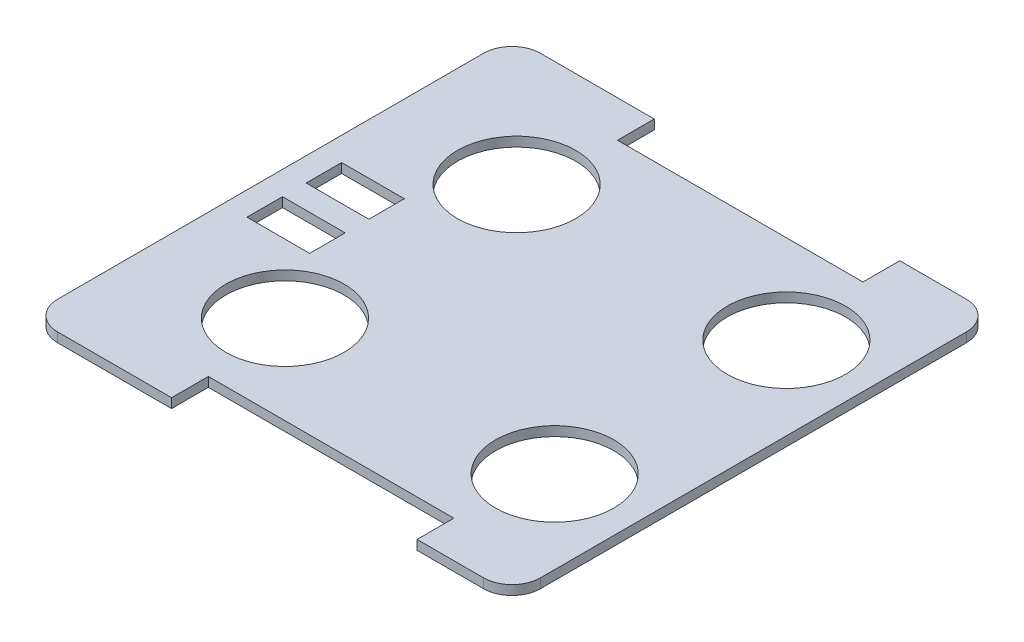
SolidWorks part; units mm, degrees
material "Aleación 1060"
ref_plane "Alzado" through (0, 0, 0) normal (0, 0, 1) x (1, 0, 0)
ref_plane "Planta" through (0, 0, 0) normal (0, 1, 0) x (1, 0, 0)
ref_plane "Vista lateral" through (0, 0, 0) normal (1, 0, 0) x (0, 0, -1)
ref_plane "Plano1" through (0, 54.7071, 0) normal (0, 1, 0) x (1, 0, 0)
sketch "Croquis1" plane through (0, 54.7071, 0) normal (0, 1, 0) x (1, 0, 0)
  line L48 (-135.857, -92.1) -> (-135.857, -55) construction
  line L55 (-135.857, -92.1) -> (71.653, -92.1) construction
  line L63 (71.653, -92.1) -> (71.653, -55) construction
  line L72 (71.653, -437.9) -> (71.653, -475) construction
  line L82 (-135.857, -437.9) -> (71.653, -437.9) construction
  line L93 (-135.857, -437.9) -> (-135.857, -475) construction
  line L105 (-232.102, -61.0045) -> (-135.857, -61.0045) construction
  line L106 (71.653, -61.0045) -> (127.898, -61.0045) construction
  line L107 (151.8935, -85) -> (151.8935, -445) construction
  line L108 (127.898, -468.9955) -> (71.653, -468.9955) construction
  line L109 (-135.857, -468.9955) -> (-232.102, -468.9955) construction
  line L110 (-256.0976, -445) -> (-256.0976, -85) construction
  line L111 (-135.857, -92.1) -> (71.653, -92.1)
  line L112 (71.653, -437.9) -> (71.653, -468.9955)
  line L113 (-135.857, -437.9) -> (71.653, -437.9)
  line L114 (-135.857, -437.9) -> (-135.857, -468.9955)
  line L115 (-135.857, -92.1) -> (-135.857, -61.0045)
  line L116 (71.653, -92.1) -> (71.653, -61.0045)
  line L117 (-232.102, -61.0045) -> (-135.857, -61.0045)
  line L118 (71.653, -61.0045) -> (127.898, -61.0045)
  line L119 (151.8935, -85) -> (151.8935, -445)
  line L120 (127.898, -468.9955) -> (71.653, -468.9955)
  line L121 (-135.857, -468.9955) -> (-232.102, -468.9955)
  line L122 (-256.0976, -445) -> (-256.0976, -85)
  arc A56 (-232.102, -61.0045) -> (-256.0976, -85) centre (-232.102, -85) ccw construction
  arc A57 (151.8935, -85) -> (127.898, -61.0045) centre (127.898, -85) ccw construction
  arc A58 (127.898, -468.9955) -> (151.8935, -445) centre (127.898, -445) ccw construction
  arc A59 (-256.0976, -445) -> (-232.102, -468.9955) centre (-232.102, -445) ccw construction
  arc A60 (-232.102, -61.0045) -> (-256.0976, -85) centre (-232.102, -85) ccw
  arc A61 (151.8935, -85) -> (127.898, -61.0045) centre (127.898, -85) ccw
  arc A62 (127.898, -468.9955) -> (151.8935, -445) centre (127.898, -445) ccw
  arc A63 (-256.0976, -445) -> (-232.102, -468.9955) centre (-232.102, -445) ccw
extrude "Saliente-Extruir1" add sketch "Croquis1" along normal mid plane 8 contours L113 L112 L120 A62 L119 A61 L118 L116 L111 L115 L117 A60 L122 A63 L121 L114
sketch "Croquis2" plane through (0, 58.7071, 0) normal (0, 1, 0) x (1, 0, 0)
  line L0 (-32.102, -92.1) -> (-32.102, -437.9) construction
  line L5 (71.653, -92.1) -> (-135.857, -92.1) construction
  line L6 (51.8935, -167.1) -> (111.8935, -167.1) construction
  line L11 (-256.0976, -265) -> (151.8935, -265) construction
  line L12 (-92.102, -92.1) -> (27.898, -92.1) construction
  line L13 (-92.102, -92.1) -> (-92.102, -244.5) construction
  line L14 (-92.102, -244.5) -> (27.898, -244.5) construction
  line L15 (27.898, -92.1) -> (27.898, -244.5) construction
  line L16 (-256.0976, -85) -> (-256.0976, -445) construction
  line L17 (151.8935, -445) -> (151.8935, -85) construction
  line L18 (-92.102, -285.5) -> (27.898, -285.5) construction
  line L19 (27.898, -437.9) -> (27.898, -285.5) construction
  line L20 (-92.102, -437.9) -> (27.898, -437.9) construction
  line L21 (-92.102, -437.9) -> (-92.102, -285.5) construction
  line L26 (111.8935, -237.1) -> (111.8935, -97.1) construction
  line L27 (51.8935, -97.1) -> (111.8935, -97.1) construction
  line L28 (51.8935, -237.1) -> (51.8935, -97.1) construction
  line L29 (51.8935, -237.1) -> (111.8935, -237.1) construction
  line L30 (-256.0976, -290) -> (-244.6304, -290) construction
  line L31 (-256.0976, -290) -> (-256.0976, -240) construction
  line L32 (-256.0976, -240) -> (-244.6304, -240) construction
  line L33 (-244.6304, -290) -> (-244.6304, -240) construction
  line L39 (-116.0976, -237.1) -> (-176.0976, -237.1) construction
  line L40 (-116.0976, -237.1) -> (-116.0976, -97.1) construction
  line L41 (-116.0976, -97.1) -> (-176.0976, -97.1) construction
  line L42 (-176.0976, -237.1) -> (-176.0976, -97.1) construction
  line L43 (-116.0976, -167.1) -> (-176.0976, -167.1) construction
  line L44 (51.8935, -292.9) -> (111.8935, -292.9) construction
  line L45 (51.8935, -292.9) -> (51.8935, -432.9) construction
  line L46 (51.8935, -432.9) -> (111.8935, -432.9) construction
  line L47 (111.8935, -292.9) -> (111.8935, -432.9) construction
  line L48 (51.8935, -362.9) -> (111.8935, -362.9) construction
  line L49 (-116.0976, -362.9) -> (-176.0976, -362.9) construction
  line L50 (-176.0976, -292.9) -> (-176.0976, -432.9) construction
  line L51 (-116.0976, -432.9) -> (-176.0976, -432.9) construction
  line L52 (-116.0976, -292.9) -> (-116.0976, -432.9) construction
  line L53 (-116.0976, -292.9) -> (-176.0976, -292.9) construction
  line L55 (-236.0976, -275) -> (-183.0976, -275)
  line L56 (-236.0976, -275) -> (-236.0976, -305)
  line L57 (-236.0976, -305) -> (-183.0976, -305)
  line L58 (-183.0976, -275) -> (-183.0976, -305)
  line L62 (-236.0976, -225) -> (-183.0976, -225)
  line L63 (-183.0976, -255) -> (-183.0976, -225)
  line L64 (-236.0976, -255) -> (-183.0976, -255)
  line L65 (-236.0976, -255) -> (-236.0976, -225)
  circle A0 centre (-146.0976, -167.1) radius 50
  circle A1 centre (81.8935, -167.1) radius 50
  circle A3 centre (81.8935, -362.9) radius 50
  circle A4 centre (-146.0976, -362.9) radius 50
  point P3 (-32.102, -437.9)
  point P44 (-256.0976, -265)
  point P51 (-32.102, -92.1)
  point P52 (-32.102, -92.1)
  point P61 (131.8935, -167.1)
  point P67 (-236.0976, -290)
  dimension "D6" = 100
  dimension "D1" = 60
  dimension "D2" = 140
  dimension "D3" = 152.4
  dimension "D4" = 120
  dimension "D5" = 50
  dimension "D7" = 20
  dimension "D8" = 53
  dimension "D9" = 30
  dimension "D10" = 20
  dimension "D11" = 75
extrude "Cortar-Extruir1" cut sketch "Croquis2" against normal up to next
